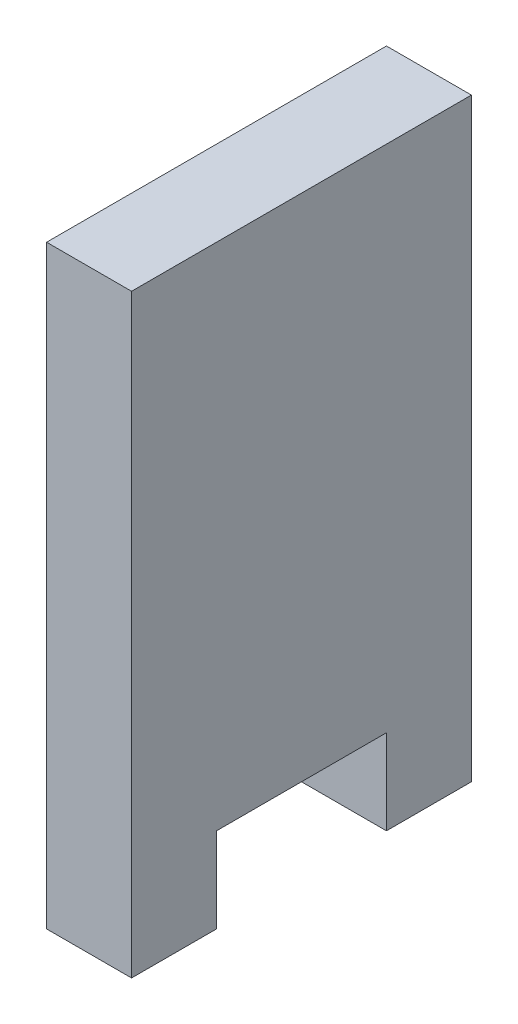
SolidWorks part; units mm, degrees
ref_plane "Front Plane" through (0, 0, 0) normal (0, 0, 1) x (1, 0, 0)
ref_plane "Top Plane" through (0, 0, 0) normal (0, 1, 0) x (1, 0, 0)
ref_plane "Right Plane" through (0, 0, 0) normal (1, 0, 0) x (0, 0, -1)
sketch "Sketch1" plane through (0, 0, 0) normal (1, 0, 0) x (0, 0, -1)
  line L1 (-12.7, -19.05) -> (12.7, -19.05)
  line L2 (-12.7, -19.05) -> (-12.7, 19.05)
  line L3 (-12.7, 19.05) -> (12.7, 19.05)
  line L4 (12.7, -19.05) -> (12.7, 19.05)
  line L5 (-12.7, -19.05) -> (12.7, 19.05) construction
  line L6 (-12.7, 19.05) -> (12.7, -19.05) construction
  line L7 (-12.7, -19.05) -> (-6.35, -19.05)
  line L8 (-12.7, -19.05) -> (-12.7, -12.7)
  line L9 (-12.7, -19.05) -> (-6.35, -19.05)
  line L10 (-12.7, -19.05) -> (-12.7, -25.4)
  line L11 (12.7, -19.05) -> (6.35, -19.05)
  line L12 (12.7, -19.05) -> (12.7, -25.4)
  line L13 (12.7, -25.4) -> (6.35, -25.4)
  line L14 (6.35, -19.05) -> (6.35, -25.4)
  line L15 (-12.7, -25.4) -> (-6.35, -25.4)
  line L16 (-6.35, -19.05) -> (-6.35, -25.4)
  point P0 (0, 0)
extrude "Boss-Extrude1" add sketch "Sketch1" along normal blind 6.35
